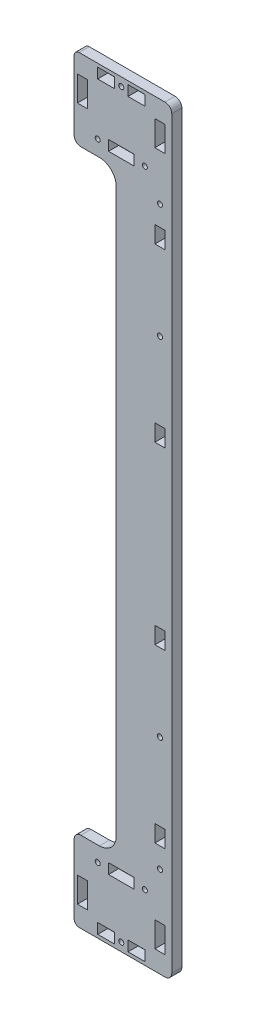
SolidWorks part; units mm, degrees
ref_plane "Front" through (0, 0, 0) normal (0, 0, 1) x (1, 0, 0)
ref_plane "Top" through (0, 0, 0) normal (0, 1, 0) x (1, 0, 0)
ref_plane "Right" through (0, 0, 0) normal (1, 0, 0) x (0, 0, -1)
sketch "Эскиз1" plane through (0, 0, 0) normal (0, 0, 1) x (1, 0, 0)
  line L0 (-5, 217) -> (-5, 223.1)
  line L1 (-5, 223.1) -> (-15, 223.1)
  line L2 (-15, 223.1) -> (-15, 217)
  line L3 (-15, 217) -> (-5, 217)
  line L4 (6.55, 183) -> (6.55, 189.1)
  line L5 (6.55, 189.1) -> (-8.55, 189.1)
  line L6 (-8.55, 189.1) -> (-8.55, 183)
  line L7 (-8.55, 183) -> (6.55, 183)
  line L8 (13, 223.1) -> (3, 223.1)
  line L9 (3, 223.1) -> (3, 217)
  line L10 (3, 217) -> (13, 217)
  line L11 (13, 217) -> (13, 223.1)
  line L12 (-27.05, 213.6) -> (-27.05, 198.6)
  line L13 (-27.05, 198.6) -> (-20.95, 198.6)
  line L14 (-20.95, 198.6) -> (-20.95, 213.6)
  line L15 (-20.95, 213.6) -> (-27.05, 213.6)
  line L16 (25.05, 198.6) -> (25.05, 213.6)
  line L17 (25.05, 213.6) -> (18.95, 213.6)
  line L18 (18.95, 213.6) -> (18.95, 198.6)
  line L19 (18.95, 198.6) -> (25.05, 198.6)
  line L20 (25, 47.1) -> (25, 57.1)
  line L21 (25, 57.1) -> (19, 57.1)
  line L22 (19, 57.1) -> (19, 47.1)
  line L23 (19, 47.1) -> (25, 47.1)
  line L24 (25, 149.1) -> (25, 159.1)
  line L25 (25, 159.1) -> (19, 159.1)
  line L26 (19, 159.1) -> (19, 149.1)
  line L27 (19, 149.1) -> (25, 149.1)
  line L28 (-29, 222.1) -> (-29, 181.1)
  line L29 (25, 225.1) -> (-26, 225.1)
  line L30 (-25, 177.1) -> (-14, 177.1)
  line L31 (-5, -217) -> (-5, -223.1)
  line L32 (-5, -223.1) -> (-15, -223.1)
  line L33 (-15, -223.1) -> (-15, -217)
  line L34 (-15, -217) -> (-5, -217)
  line L35 (6.55, -183) -> (6.55, -189.1)
  line L36 (6.55, -189.1) -> (-8.55, -189.1)
  line L37 (-8.55, -189.1) -> (-8.55, -183)
  line L38 (-8.55, -183) -> (6.55, -183)
  line L39 (13, -223.1) -> (3, -223.1)
  line L40 (3, -223.1) -> (3, -217)
  line L41 (3, -217) -> (13, -217)
  line L42 (13, -217) -> (13, -223.1)
  line L43 (-27.05, -213.6) -> (-27.05, -198.6)
  line L44 (-27.05, -198.6) -> (-20.95, -198.6)
  line L45 (-20.95, -198.6) -> (-20.95, -213.6)
  line L46 (-20.95, -213.6) -> (-27.05, -213.6)
  line L47 (25.05, -198.6) -> (25.05, -213.6)
  line L48 (25.05, -213.6) -> (18.95, -213.6)
  line L49 (18.95, -213.6) -> (18.95, -198.6)
  line L50 (18.95, -198.6) -> (25.05, -198.6)
  line L51 (25, -47.1) -> (25, -57.1)
  line L52 (25, -57.1) -> (19, -57.1)
  line L53 (19, -57.1) -> (19, -47.1)
  line L54 (19, -47.1) -> (25, -47.1)
  line L55 (25, -149.1) -> (25, -159.1)
  line L56 (25, -159.1) -> (19, -159.1)
  line L57 (19, -159.1) -> (19, -149.1)
  line L58 (19, -149.1) -> (25, -149.1)
  line L59 (-29, -222.1) -> (-29, -181.1)
  line L60 (25, -225.1) -> (-26, -225.1)
  line L61 (-25, -177.1) -> (-14, -177.1)
  line L62 (-4, 167.1) -> (-4, -167.1)
  line L63 (29, -221.1) -> (29, 221.1)
  circle A0 centre (22, 171.1) radius 1.5
  circle A1 centre (13, 186.1) radius 1.5
  circle A2 centre (-1, 220.1) radius 1.5
  circle A3 centre (-15, 186.1) radius 1.5
  arc A4 (-29, 181.1) -> (-25, 177.1) centre (-25, 181.1) ccw
  arc A5 (29, 221.1) -> (25, 225.1) centre (25, 221.1) ccw
  circle A6 centre (22, 103.1) radius 1.55
  arc A7 (-26, 225.1) -> (-29, 222.1) centre (-26, 222.1) ccw
  circle A8 centre (22, -171.1) radius 1.5
  circle A9 centre (13, -186.1) radius 1.5
  circle A10 centre (-1, -220.1) radius 1.5
  circle A11 centre (-15, -186.1) radius 1.5
  arc A12 (-25, -177.1) -> (-29, -181.1) centre (-25, -181.1) ccw
  arc A13 (25, -225.1) -> (29, -221.1) centre (25, -221.1) ccw
  circle A14 centre (22, -103.1) radius 1.55
  arc A15 (-29, -222.1) -> (-26, -225.1) centre (-26, -222.1) ccw
  arc A16 (-14, -177.1) -> (-4, -167.1) centre (-14, -167.1) ccw
  arc A17 (-4, 167.1) -> (-14, 177.1) centre (-14, 167.1) ccw
extrude "Бобышка-Вытянуть1" add sketch "Эскиз1" along normal blind 6
